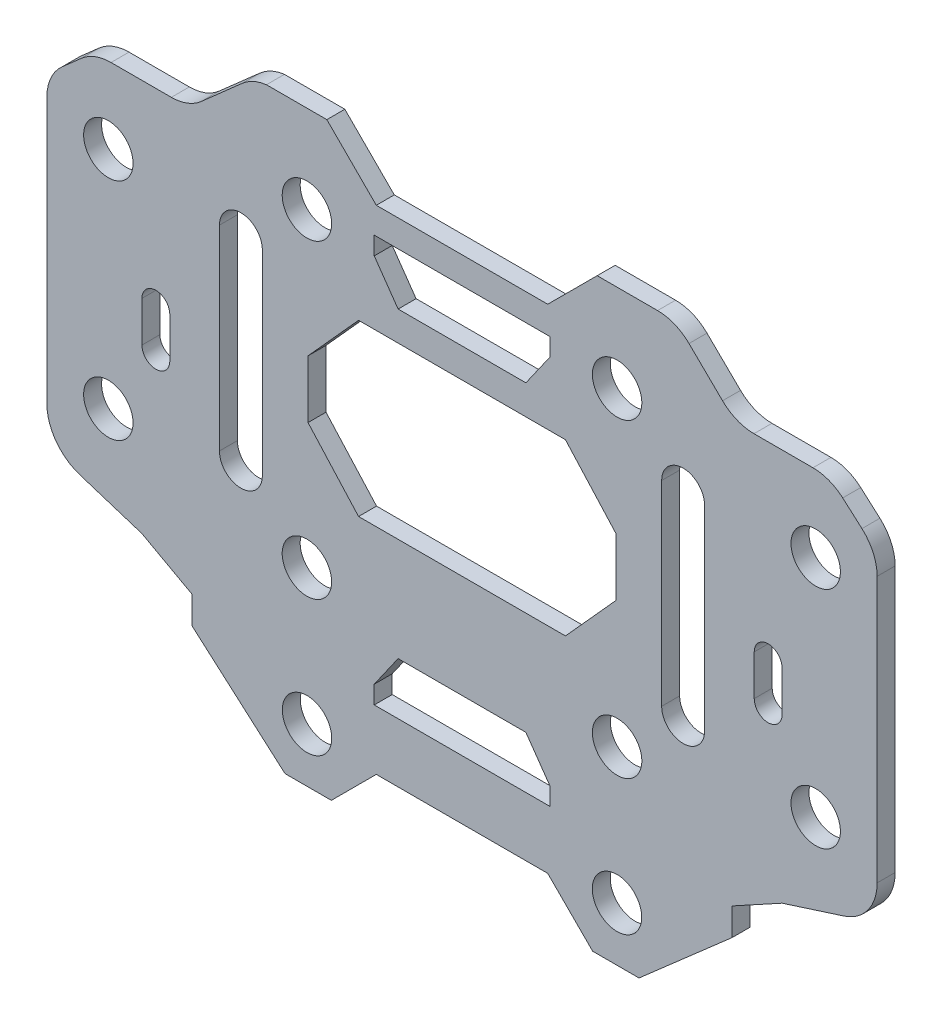
SolidWorks part; units mm, degrees
material "Thornel VCB-20 碳布"
ref_plane "前视基准面" through (0, 0, 0) normal (0, 0, 1) x (1, 0, 0)
ref_plane "上视基准面" through (0, 0, 0) normal (0, 1, 0) x (1, 0, 0)
ref_plane "右视基准面" through (0, 0, 0) normal (1, 0, 0) x (0, 0, -1)
sketch "草图1" plane through (0, 0, 0) normal (0, 0, 1) x (1, 0, 0)
  line L257 (0, -1000) -> (0, 49000) construction
  line L346 (0, 0) -> (635.1265, 0) construction
  line L351 (-46.1708, 93.9243) -> (-46.1708, 145) construction
  line L358 (-27.9426, 92.9426) -> (-32.5, 97.5) construction
  line L394 (-24.4478, 142.8678) -> (-29.0158, 138.8343)
  line L411 (-32.3253, 137.5823) -> (-39.0335, 137.5823)
  line L414 (-42.3429, 136.3303) -> (-44.4803, 134.4431)
  line L445 (-46.1708, 130.695) -> (-46.1708, 101.1668)
  line L472 (42.3429, 136.3303) -> (44.4803, 134.4431)
  line L494 (46.1729, 155.4291) -> (33.7932, 145.5483) construction
  line L496 (32.4724, 137.5823) -> (39.0335, 137.5823)
  line L497 (25.2455, 142.6568) -> (28.9763, 139.0078)
  line L498 (27.9426, 92.9426) -> (32.5, 97.5) construction
  line L501 (-46.2756, 154.6927) -> (-33.8959, 144.8119) construction
  line L595 (-39.3354, 129.0823) -> (-39.3354, 104.0823) construction
  line L626 (-31.6538, 83.28) -> (-46.1708, 93.9243) construction
  line L628 (-39.3354, 116.5823) -> (0, 116.5823) construction
  line L629 (-15.0322, 144.0823) -> (-9.5322, 138.5823)
  line L630 (-9.5322, 138.5823) -> (9.5322, 138.5823)
  line L631 (15.0322, 144.0823) -> (9.5322, 138.5823)
  line L633 (-21.7494, 144.0823) -> (-15.0322, 144.0823)
  line L635 (15.0322, 144.0823) -> (21.7494, 144.0823)
  line L641 (-9.5322, 83.7633) -> (9.5322, 83.7633)
  line L643 (-9.5322, 83.7633) -> (-14.5322, 78.7633)
  line L644 (30.4418, 78.7633) -> (14.5322, 78.7633) construction
  line L645 (9.5322, 83.7633) -> (14.5322, 78.7633)
  line L646 (7.1054, 96.1323) -> (-7.1054, 96.1323)
  line L647 (-7.1054, 96.1323) -> (-9.7615, 92.339)
  line L648 (-9.7615, 92.339) -> (-9.7615, 90.339)
  line L649 (-9.7615, 90.339) -> (9.7615, 90.339)
  line L652 (9.7615, 92.339) -> (9.7615, 90.339)
  line L653 (7.1054, 96.1323) -> (9.7615, 92.339)
  line L666 (-35.6, 116.5823) -> (-35.6, 112.0823)
  line L668 (-32.5, 116.5823) -> (-32.5, 112.0823)
  line L670 (35.6, 116.5823) -> (35.6, 112.0823)
  line L671 (32.5, 116.5823) -> (32.5, 112.0823)
  line L681 (-19.6882, 78.7633) -> (-14.5322, 78.7633)
  line L686 (14.5322, 78.7633) -> (19.6882, 78.7633)
  line L687 (-42.4964, 96.1323) -> (-35.6, 93.9243)
  line L688 (-35.6, 93.9243) -> (-30.0524, 90.888)
  line L691 (-30.0524, 90.888) -> (-30.0524, 87.8422)
  line L692 (-30.0524, 87.8422) -> (-19.6882, 78.7633)
  line L693 (30.0524, 87.8422) -> (19.6882, 78.7633)
  line L694 (30.0524, 90.888) -> (30.0524, 87.8422)
  line L695 (35.6, 93.9243) -> (30.0524, 90.888)
  line L696 (42.4964, 96.1323) -> (35.6, 93.9243)
  line L697 (46.1708, 130.695) -> (46.1708, 101.1668)
  line L700 (-17.1276, 113.853) -> (-11.5061, 107.6186)
  line L701 (-11.5061, 107.6186) -> (11.5061, 107.6186)
  line L706 (17.1276, 113.853) -> (11.5061, 107.6186)
  line L709 (-7.1054, 129.7982) -> (7.1054, 129.7982)
  line L710 (7.1054, 129.7982) -> (9.7615, 133.5915)
  line L711 (9.7615, 133.5915) -> (9.7615, 135.5915)
  line L712 (9.7615, 135.5915) -> (-9.7615, 135.5915)
  line L713 (-9.7615, 133.5915) -> (-9.7615, 135.5915)
  line L714 (-7.1054, 129.7982) -> (-9.7615, 133.5915)
  line L715 (-24.5927, 117.0678) -> (26.26, 117.0678) construction
  line L717 (17.1276, 113.853) -> (17.1276, 120.2826)
  line L719 (-17.1276, 113.853) -> (-17.1276, 120.2826)
  line L720 (17.1276, 120.2826) -> (11.5061, 126.517)
  line L721 (-17.1276, 120.2826) -> (-11.5061, 126.517)
  line L722 (-11.5061, 126.517) -> (11.5061, 126.517)
  line L723 (-24.5927, 127.9437) -> (-24.5927, 106.192) construction
  line L724 (-22.2052, 127.9437) -> (-22.2052, 106.192)
  line L725 (-26.9801, 127.9437) -> (-26.9801, 106.192)
  line L726 (24.5927, 127.9437) -> (24.5927, 106.192) construction
  line L727 (22.2052, 127.9437) -> (22.2052, 106.192)
  line L728 (26.9801, 127.9437) -> (26.9801, 106.192)
  circle A384 centre (39.3354, 129.0823) radius 2.75
  circle A385 centre (39.3354, 104.0823) radius 2.75
  circle A390 centre (17.238, 84.7633) radius 2.75
  circle A420 centre (-17.238, 84.7633) radius 2.75
  circle A421 centre (-39.3354, 104.0823) radius 2.75
  circle A422 centre (-39.3354, 129.0823) radius 2.75
  arc A453 (32.7926, 143.0294) -> (32.5, 97.5) centre (-120.6696, 121.25) cw construction
  arc A454 (-32.8936, 142.3057) -> (-32.5, 97.5) centre (120.6696, 121.25) ccw construction
  arc A455 (-27.9426, 92.9426) -> (27.9426, 92.9426) centre (0, 290.981) ccw construction
  arc A456 (33.7932, 145.5483) -> (32.7926, 143.0294) centre (35.4973, 143.4132) ccw construction
  arc A457 (-32.8936, 142.3057) -> (-33.8959, 144.8119) centre (-35.6, 142.6768) ccw construction
  arc A473 (-44.4803, 134.4431) -> (-46.1708, 130.695) centre (-41.1708, 130.695) ccw
  arc A474 (-39.0335, 137.5823) -> (-42.3429, 136.3303) centre (-39.0335, 132.5823) ccw
  arc A475 (46.1708, 130.695) -> (44.4803, 134.4431) centre (41.1708, 130.695) ccw
  arc A476 (42.3429, 136.3303) -> (39.0335, 137.5823) centre (39.0335, 132.5823) ccw
  arc A477 (32.4724, 137.5823) -> (28.9763, 139.0078) centre (32.4724, 142.5823) cw
  arc A478 (-29.0158, 138.8343) -> (-32.3253, 137.5823) centre (-32.3253, 142.5823) cw
  arc A479 (25.2455, 142.6568) -> (21.7494, 144.0823) centre (21.7494, 139.0823) ccw
  arc A480 (-21.7494, 144.0823) -> (-24.4478, 142.8678) centre (-21.1384, 139.1198) ccw
  arc A481 (-35.6, 116.5823) -> (-32.5, 116.5823) centre (-34.05, 116.5823) cw
  arc A484 (-35.6, 112.0823) -> (-32.5, 112.0823) centre (-34.05, 112.0823) ccw
  arc A486 (35.6, 116.5823) -> (32.5, 116.5823) centre (34.05, 116.5823) ccw
  arc A487 (35.6, 112.0823) -> (32.5, 112.0823) centre (34.05, 112.0823) cw
  arc A490 (-46.1708, 101.1668) -> (-42.4964, 96.1323) centre (-40.8846, 101.1668) ccw
  arc A491 (46.1708, 101.1668) -> (42.4964, 96.1323) centre (40.8846, 101.1668) cw
  circle A492 centre (17.25, 134.3178) radius 2.75
  circle A493 centre (17.25, 99.8178) radius 2.75
  circle A494 centre (-17.25, 99.8178) radius 2.75
  circle A495 centre (-17.25, 134.3178) radius 2.75
  arc A496 (-22.2052, 127.9437) -> (-26.9801, 127.9437) centre (-24.5927, 127.9437) ccw
  arc A497 (-26.9801, 106.192) -> (-22.2052, 106.192) centre (-24.5927, 106.192) ccw
  arc A498 (22.2052, 127.9437) -> (26.9801, 127.9437) centre (24.5927, 127.9437) cw
  arc A499 (26.9801, 106.192) -> (22.2052, 106.192) centre (24.5927, 106.192) cw
  point P15 (0, 78.5133)
  point P20 (-24.5927, 117.0678)
  point P31 (-12.3077, 124.3848)
  point P46 (-46.1708, 132.9503)
  point P50 (-40.925, 137.5823)
  point P53 (46.1708, 132.9503)
  point P56 (40.925, 137.5823)
  point P59 (30.4337, 137.5823)
  point P62 (-30.4337, 137.5823)
  point P65 (23.8205, 144.5823)
  point P69 (-23.8205, 144.5823)
  point P76 (0, 138.5823)
  point P90 (0, 90.339)
  point P92 (0, 96.1323)
  point P118 (0.085, 119.8323)
  point P121 (0, 107.6186)
  point P123 (24.5927, 117.0678)
  point P133 (0, 135.5915)
  point P136 (0, 129.7982)
  point P144 (17.1276, 117.0678)
  point P151 (-17.1276, 117.0678)
  point P155 (-34.05, 93.9243)
  point P156 (-35.6, 93.9243)
  point P157 (-30.0524, 87.8422)
  point P162 (-18.2008, 117.9136)
  point P163 (-9.7615, 105.7684)
  point P164 (-17.3576, 118.5631)
  dimension "D1" = 84.7633
  dimension "D2" = 17.238
  dimension "D5" = 44.319
  dimension "D6" = 19.319
  dimension "D7" = 22.0974
  dimension "D8" = 22.0974
  dimension "D9" = 6.5
  dimension "D11" = 46.1708
  dimension "D15" = 33.5
  dimension "D17" = 6
  dimension "D38" = 5.5
  dimension "D39" = 155
  dimension "D40" = 200
  dimension "D27" = 135
  dimension "D31" = 1.55
  dimension "D18" = 34.5
  dimension "D10" = 138.556
  dimension "D12" = 31.6538
  dimension "D13" = 93.9243
  dimension "D14" = 83.28
  dimension "D16" = 5.5
  dimension "D19" = 34.5
  dimension "D25" = 5
  dimension "D26" = 135
  dimension "D28" = 125
  dimension "D29" = 2
  dimension "D30" = 20.45
  dimension "D32" = 32.5
  dimension "D33" = 4.5
extrude "凸台-拉伸1" add sketch "草图1" along normal blind 2
